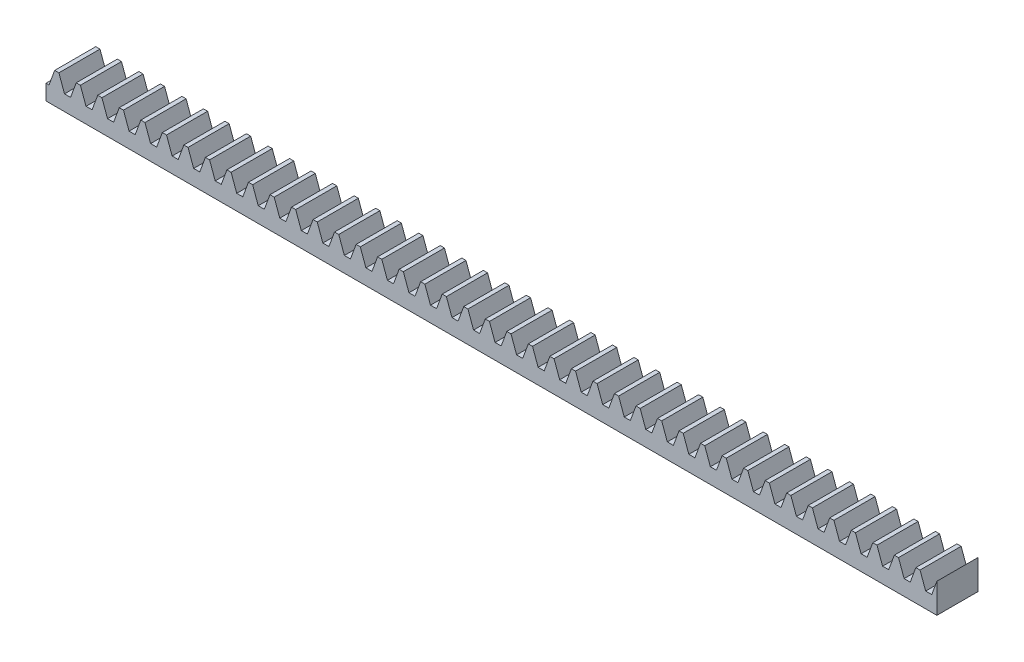
SolidWorks part; units mm, degrees
extrude "Blank" add sketch "BlankSke" against normal blind 6
sketch "BlankSke" plane through (0, 0, 0) normal (0, 0, 1) x (1, 0, 0)
  line L1 (0, 0) -> (130, 0)
  line L2 (0, 0) -> (0, 4.5)
  line L3 (0, 4.5) -> (130, 4.5)
  line L4 (130, 0) -> (130, 4.5)
  dimension "Length" = 130
  dimension "Blank_height" = 4.5
ref_plane "Plane1" through (0, 0, 0) normal (0, 0, 1) x (1, 0, 0)
ref_plane "Plane2" through (0, 0, 0) normal (0, 1, 0) x (1, 0, 0)
ref_plane "Plane3" through (0, 0, 0) normal (1, 0, 0) x (0, 0, -1)
sketch "HoldingSke" plane through (0, 0, 0) normal (0, 1, 0) x (1, 0, 0)
  line L0 (0, 0) -> (0.1392, 0.9903)
  line L1 (-15, 0) -> (100, 0) construction
  line L2 (0, 0) -> (-2.1039, 2.3779)
  line L3 (0, 0) -> (-11.863, 4.5341)
  line L4 (0, 0) -> (6.316, 5.8897)
  line L5 (0, 0) -> (-23.7986, -8.8762)
  line L6 (0, 0) -> (-10.5278, -7.1032)
  line L9 (-71.009, 38.7566) -> (51.1511, 83.2192)
  line L10 (-76.2, 3.3779) -> (-72.7, 3.3779)
  line L11 (0, 0) -> (-6, 0)
  line L12 (-76.2, 101.6) -> (-76.162, 101.6)
  line L13 (24.9733, 27.94) -> (52.9518, 28.4284)
  line L14 (24.9733, 27.94) -> (24.9743, 27.94)
  line L15 (24.9733, 27.94) -> (100.4006, 29.5858)
  circle A0 centre (0, 0) radius 19.05
  circle A1 centre (0, 0) radius 1.75
  circle A2 centre (0, 0) radius 12.7
  dimension "MPH" = 3.5
  dimension "Diameter" = 38.1
  dimension "Num_teeth" = 43
  dimension "Pitch" = 1
  dimension "Show_teeth" = 998
  dimension "Thickness" = 12.7
  dimension "Ap" = 20
  dimension "Pitch_height" = 3.5
  dimension "Width" = 6
  dimension "Backlash" = 0.038
  dimension "Addendum_fac" = 1
  dimension "Dedendum_fac" = 1.25
  dimension "Clearance_fac" = 0.25
  dimension "Dedendum_add" = 0.001
  dimension "Length" = 130
  dimension "Module" = 1
sketch "TooCutSkeIll" plane through (0, 0, 0) normal (0, 0, 1) x (1, 0, 0)
  line L0 (-1.2538, 4.4737) -> (-0.5045, 2.4152)
  line L1 (-0.2687, 2.25) -> (0.2687, 2.25)
  line L2 (0.5045, 2.4152) -> (1.2538, 4.4737)
  line L3 (130, 4.5) -> (0, 4.5) construction
  line L4 (0, 0) -> (0, 64.897) construction
  line L5 (-13.208, 3.5) -> (12.954, 3.5) construction
  line L6 (0, 0) -> (130, 0) construction
  line L7 (0.8994, 3.5) -> (0.8994, 48.7463) construction
  line L8 (-0.8994, 3.5) -> (-0.8994, 48.7463) construction
  line L9 (1.2914, 4.5) -> (1.2914, 4.5254)
  line L10 (-1.2914, 4.5) -> (-1.2914, 4.5254)
  line L11 (-1.2914, 4.5254) -> (1.2914, 4.5254)
  arc A0 (0.2687, 2.25) -> (0.5045, 2.4152) centre (0.2687, 2.501) ccw
  arc A1 (-0.5045, 2.4152) -> (-0.2687, 2.25) centre (-0.2687, 2.501) ccw
  arc A2 (1.2914, 4.5) -> (1.2538, 4.4737) centre (1.2914, 4.46) ccw
  arc A3 (-1.2538, 4.4737) -> (-1.2914, 4.5) centre (-1.2914, 4.46) ccw
  dimension "Pitch_height" = 3.5
  dimension "Addendum_plus" = 1.0254
  dimension "Pressure_angle" = 20
  dimension "Gap_width" = 1.7988
  dimension "Dedendum" = 1.25
extrude "ToothCutIll" [suppressed] cut sketch "TooCutSkeIll" against normal through all
sketch "TooCutSkeSim" plane through (0, 0, 0) normal (0, 0, 1) x (1, 0, 0)
  line L0 (0.4444, 2.25) -> (-0.4444, 2.25)
  line L1 (1.2726, 4.5254) -> (0.4444, 2.25)
  line L2 (0, 17.4625) -> (0, 53.467) construction
  line L3 (1.2726, 4.5254) -> (-1.2726, 4.5254)
  line L6 (-1.2726, 4.5254) -> (-0.4444, 2.25)
  line L9 (-0.8994, 3.5) -> (0.8994, 3.5) construction
  line L10 (0, 0) -> (130, 0) construction
  line L11 (0.8994, 3.5) -> (0.8994, 53.467) construction
  line L12 (-0.8994, 3.5) -> (-0.8994, 53.467) construction
  dimension "Pitch_height" = 3.5
  dimension "Addendum_plus" = 1.0254
  dimension "Pressure_angle" = 20
  dimension "Gap_width" = 1.7988
  dimension "Dedendum" = 1.25
extrude "ToothCutSim" cut sketch "TooCutSkeSim" against normal through all
pattern_linear "TeethCuts" count 42 spacing 3.1416 along (1, 0, 0) of "ToothCutIll", "ToothCutSim"
sketch "草图1" plane through (0, 0, 0) normal (0, 0, 1) x (1, 0, 0)
  line L0 (1.2634, 4.5) -> (0.4444, 2.25) construction
  line L1 (0.4444, 2.25) -> (0, 2.25) construction
  line L2 (0, 2.25) -> (0, 4.5) construction
  line L3 (0, 3.375) -> (0.8539, 3.375) construction
  line L4 (0, 4.5) -> (1.2634, 4.5) construction
equation "' \"Module@HoldingSke\" = 6.35"
equation "' \"Num_teeth@HoldingSke\" = 12"
equation "' \"Ap@HoldingSke\" =  20"
equation "' \"Ap@HoldingSke\" = 20"
equation "' \"Width@HoldingSke\" = 0.25 * 25.4"
equation "' \"Show_teeth@HoldingSke\" = 500"
equation "' \"Backlash@HoldingSke\" = 0.009 * 25.4"
equation "' \"Addendum_fac@HoldingSke\" = 1.0"
equation "' \"Dedendum_fac@HoldingSke\" = 1.25"
equation "' \"Dedendum_add@HoldingSke\" = 0.00005 * 25.4"
equation "' \"Clearance_fac@HoldingSke\" = 0.25"
equation "' \"Pitch_height@HoldingSke\" = 1 * 25.4"
equation "' \"Length@HoldingSke\" = 4.71 * 25.4"
equation "\"Pitch@HoldingSke\" = 1 / \"Module@HoldingSke\""
equation "\"MPH@HoldingSke\" = \"Dedendum_fac@HoldingSke\" / \"Pitch@HoldingSke\" + 2 * \"Dedendum_add@HoldingSke\" + 0.002 * 25.4"
equation "\"MPH@HoldingSke\" = ((sgn( \"MPH@HoldingSke\" - \"Pitch_height@HoldingSke\")+1)*( \"MPH@HoldingSke\" - \"Pitch_height@HoldingSke\"))/2 + \"Pitch_height@HoldingSke\""
equation "\"Blank_height@BlankSke\" = \"Pitch_height@HoldingSke\" + \"Addendum_fac@HoldingSke\"  / \"Pitch@HoldingSke\" "
equation "\"Length@BlankSke\" =  \"Length@HoldingSke\""
equation "\"Face_width@Blank\" = \"Width@HoldingSke\""
equation "\"Pressure_angle@TooCutSkeIll\" = \"Ap@HoldingSke\""
equation "\"Addendum_plus@TooCutSkeIll\" =  \"Addendum_fac@HoldingSke\"  / \"Pitch@HoldingSke\" + 0.001 *25.4"
equation "\"Dedendum@TooCutSkeIll\" = \"Dedendum_fac@HoldingSke\"  / \"Pitch@HoldingSke\""
equation "\"Pitch_height@TooCutSkeIll\" =  \"MPH@HoldingSke\""
equation "\"Gap_width@TooCutSkeIll\" = 3.14159265 / 2 / \"Pitch@HoldingSke\" + 6 * \"Backlash@HoldingSke\""
equation "\"Pressure_angle@TooCutSkeSim\" = \"Ap@HoldingSke\""
equation "\"Addendum_plus@TooCutSkeSim\" =  \"Addendum_fac@HoldingSke\"  / \"Pitch@HoldingSke\" + 0.001 * 25.4"
equation "\"Dedendum@TooCutSkeSim\" = \"Dedendum_fac@HoldingSke\"  / \"Pitch@HoldingSke\""
equation "\"Pitch_height@TooCutSkeSim\" =  \"MPH@HoldingSke\""
equation "\"Gap_width@TooCutSkeSim\" = 3.14159265 / 2 / \"Pitch@HoldingSke\" + 6 * \"Backlash@HoldingSke\""
equation "\"Root_fillet@TooCutSkeIll\" = \"Clearance_fac@HoldingSke\" / \"Pitch@HoldingSke\" + \"Dedendum_add@HoldingSke\""
equation "\"Break_rad@TooCutSkeIll\" = 0.02 / \"Pitch@HoldingSke\" * 2"
equation "\"Linear_pitch@TeethCuts\" = 3.14159265 / \"Pitch@HoldingSke\""
equation "\"Num_teeth@HoldingSke\" = int( ( \"Length@HoldingSke\" + 0 ) / (3.14159265 / \"Pitch@HoldingSke\")) + 0.9999  + 1"
equation " \"Num_teeth@TeethCuts\" = int( \"Show_teeth@HoldingSke\" ) + 1"
equation " \"Num_teeth@TeethCuts\" = ((sgn( \"Num_teeth@TeethCuts\" - \"Num_teeth@HoldingSke\" )-1)*( \"Num_teeth@TeethCuts\" - \"Num_teeth@HoldingSke\" ))/-2+ \"Num_teeth@HoldingSke\""
equation " \"Num_teeth@TeethCuts\" = ((sgn( \"Num_teeth@TeethCuts\" - 2.0)+1)*( \"Num_teeth@TeethCuts\" - 2.0))/2 +2.0"
